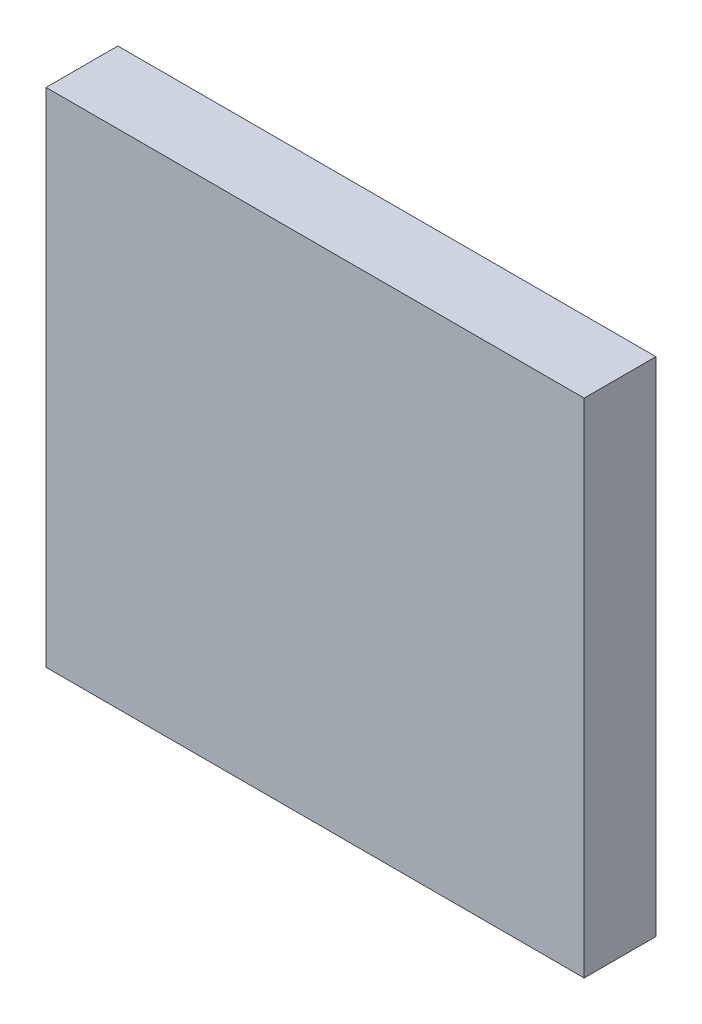
SolidWorks part; units mm, degrees
ref_plane "Front Plane" through (0, 0, 0) normal (0, 0, 1) x (1, 0, 0)
ref_plane "Top Plane" through (0, 0, 0) normal (0, 1, 0) x (1, 0, 0)
ref_plane "Right Plane" through (0, 0, 0) normal (1, 0, 0) x (0, 0, -1)
sketch "Sketch1" plane through (0, 0, 0) normal (0, 0, 1) x (1, 0, 0)
  line L1 (-75, -70) -> (75, -70)
  line L2 (-75, -70) -> (-75, 70)
  line L3 (-75, 70) -> (75, 70)
  line L4 (75, -70) -> (75, 70)
  line L5 (-75, -70) -> (75, 70) construction
  line L6 (-75, 70) -> (75, -70) construction
  point P0 (0, 0)
extrude "Boss-Extrude1" add sketch "Sketch1" along normal blind 20
